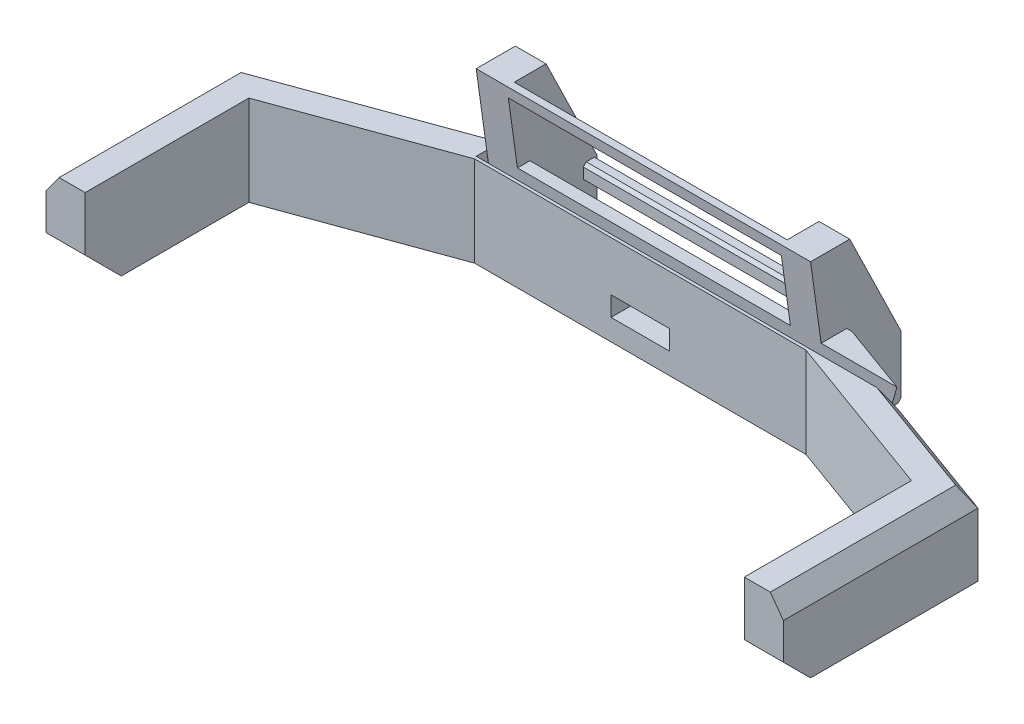
SolidWorks part; units mm, degrees
ref_plane "Front Plane" through (0, 0, 0) normal (0, 0, 1) x (1, 0, 0)
ref_plane "Top Plane" through (0, 0, 0) normal (0, 1, 0) x (1, 0, 0)
ref_plane "Right Plane" through (0, 0, 0) normal (1, 0, 0) x (0, 0, -1)
sketch "Sketch2" plane through (0, 0, 0) normal (0, 1, 0) x (1, 0, 0)
  line L0 (-1100, -366.1545) -> (-1100, 177.4707)
  line L1 (-1100, 177.4707) -> (-550, 377.4707)
  line L2 (-550, 377.4707) -> (550, 377.4707)
  line L3 (550, 377.4707) -> (1100, 177.4707)
  line L4 (1100, 177.4707) -> (1100, -377.4707)
  line L5 (0, -626.2815) -> (0, 867.8221) construction
  line L6 (-1230, -366.1545) -> (-1230, 268.5262)
  line L7 (-1230, 268.5262) -> (-572.9027, 507.4707)
  line L8 (-572.9027, 507.4707) -> (572.9027, 507.4707)
  line L9 (572.9027, 507.4707) -> (1230, 268.5262)
  line L10 (1230, 268.5262) -> (1230, -377.4707)
  line L11 (-1230, -366.1545) -> (-1100, -366.1545)
  line L12 (1100, -377.4707) -> (1230, -377.4707)
  point P9 (0, 377.4707)
  dimension "D1" = 130
extrude "Boss-Extrude1" add sketch "Sketch2" along normal blind 300
fillet "Chamfer1" radius 30 5 edges at (-901.4514, 0, -387.9984) (-1230, 0, 48.8141) (0, 0, -507.4707) (1230, 0, 54.4722) (901.4514, 0, -387.9984) profile chamfer
chamfer "Chamfer2" distance 120 angle 45 2 edges at (-1150, 0, 366.1545) (1150, 0, 377.4707)
sketch "Sketch3" plane through (0, 0, -507.4707) normal (0, 0, -1) x (-1, 0, 0)
  line L0 (567.6175, 0) -> (-567.6175, 0) construction
  line L1 (-555.1604, 551.8427) -> (-453.2203, 551.8427)
  line L2 (-555.1604, 551.8427) -> (-555.1604, 0)
  line L3 (-555.1604, 0) -> (-453.2203, 0)
  line L4 (-453.2203, 551.8427) -> (-453.2203, 0)
  line L5 (0, 857.663) -> (0, -558.4781) construction
  line L6 (555.1604, 551.8427) -> (453.2203, 551.8427)
  line L7 (555.1604, 551.8427) -> (555.1604, 0)
  line L8 (555.1604, 0) -> (453.2203, 0)
  line L9 (453.2203, 551.8427) -> (453.2203, 0)
  point P13 (-555.1604, 0)
extrude "Boss-Extrude2" add sketch "Sketch3" along normal blind 180 and the other way blind 120
sketch "Sketch5" plane through (-555.1604, 0, 0) normal (-1, 0, 0) x (0, 0, 1)
  line L0 (-387.4707, 551.8427) -> (-433.4972, 219.8641)
  line L1 (-433.4972, 219.8641) -> (-387.4707, 300)
  line L2 (-387.4707, 300) -> (-387.4707, 551.8427)
extrude "Cut-Extrude7" cut sketch "Sketch5" against normal through all
chamfer "Chamfer3" distance 170 angle 64 2 edges at (-504.1903, 551.8427, -687.4707) (504.1903, 551.8427, -687.4707)
sketch "Sketch6" plane through (-453.2203, 0, 0) normal (1, 0, 0) x (0, 0, -1)
  line L0 (387.4707, 551.8427) -> (393.758, 506.4936)
  line L1 (422.3869, 300) -> (387.4707, 551.8427) construction
  line L2 (393.758, 506.4936) -> (421.6998, 506.4936)
  line L3 (421.6998, 506.4936) -> (421.6998, 551.8427)
  line L4 (387.4707, 551.8427) -> (517.4707, 551.8427) construction
  line L5 (421.6998, 551.8427) -> (387.4707, 551.8427)
  line L6 (687.4707, 203.291) -> (641.0284, 203.291)
  line L7 (641.0284, 203.291) -> (641.0284, 148.3016)
  line L8 (641.0284, 148.3016) -> (687.4707, 148.3016)
  line L9 (687.4707, 203.291) -> (687.4707, 0) construction
  line L10 (687.4707, 148.3016) -> (687.4707, 203.291)
  line L11 (687.4707, 0) -> (641.0284, 0)
  line L12 (477.4707, 0) -> (687.4707, 0) construction
  line L13 (641.0284, 0) -> (641.0284, 57.6558)
  line L14 (641.0284, 57.6558) -> (687.4707, 57.6558)
  line L15 (687.4707, 57.6558) -> (687.4707, 0)
extrude "Boss-Extrude3" add sketch "Sketch6" along normal up to surface (906.4405 mm away) up to face at (453.2203, 242.1221, -524.3352)
chamfer "Chamfer5" distance 10 angle 45 11 edges at (0, 506.4936, -421.6998) (0, 506.4936, -393.758) (0, 551.8427, -421.6998) (0, 148.3016, -641.0284) (0, 148.3016, -687.4707) (0, 57.6558, -641.0284) (0, 0, -687.4707) (0, 0, -641.0284) (0, 57.6558, -687.4707) (0, 203.291, -641.0284) (0, 203.291, -687.4707)
sketch "Sketch7" plane through (0, 0, -507.4707) normal (0, 0, -1) x (-1, 0, 0)
  line L0 (453.2203, 148.3016) -> (-453.2203, 148.3016) construction
  line L1 (-179.9048, 148.3016) -> (179.9048, 148.3016)
  line L2 (-179.9048, 148.3016) -> (-179.9048, 57.6558)
  line L3 (-179.9048, 57.6558) -> (179.9048, 57.6558)
  line L4 (179.9048, 148.3016) -> (179.9048, 57.6558)
  line L5 (-453.2203, 57.6558) -> (453.2203, 57.6558) construction
  line L6 (-453.2203, 229.9647) -> (-453.2203, -108.7143) construction
  line L7 (-453.2203, 551.8427) -> (-453.2203, 203.291) construction
  line L8 (453.2203, 271.8323) -> (453.2203, -96.7521) construction
  line L9 (453.2203, 203.291) -> (453.2203, 551.8427) construction
  line L10 (0, -117.6859) -> (0, 348.0911) construction
extrude "Boss-Extrude4" add sketch "Sketch7" along normal blind 20
sketch "Sketch8" plane through (0, 0, -527.4707) normal (0, 0, -1) x (-1, 0, 0)
  line L0 (0, 287.0499) -> (0, -219.5145) construction
  line L1 (-97.5, 135.4787) -> (97.5, 135.4787)
  line L2 (-97.5, 135.4787) -> (-97.5, 70.4787)
  line L3 (-97.5, 70.4787) -> (97.5, 70.4787)
  line L4 (97.5, 135.4787) -> (97.5, 70.4787)
  line L5 (-179.9048, 102.9787) -> (179.9048, 102.9787) construction
  line L6 (-179.9048, 148.3016) -> (-179.9048, 57.6558) construction
  line L7 (179.9048, 57.6558) -> (179.9048, 148.3016) construction
  dimension "D1" = 65
  dimension "D2" = 195
extrude "Cut-Extrude8" cut sketch "Sketch8" against normal blind 392
sketch "Sketch9" plane through (0, 0, -421.6998) normal (0, 0, -1) x (-1, 0, 0)
  line L1 (-420.801, 536.7594) -> (-296.46, 536.7594)
  line L2 (-420.801, 536.7594) -> (-420.801, 520.5222)
  line L3 (-420.801, 520.5222) -> (-296.46, 520.5222)
  line L4 (-296.46, 536.7594) -> (-296.46, 520.5222)
  line L6 (-180.801, 520.5222) -> (-56.46, 520.5222)
  line L11 (-180.801, 536.7594) -> (-56.46, 536.7594)
  line L12 (-56.46, 536.7594) -> (-56.46, 520.5222)
  line L13 (-180.801, 536.7594) -> (-180.801, 520.5222)
  line L14 (59.199, 520.5222) -> (183.54, 520.5222)
  line L15 (59.199, 536.7594) -> (183.54, 536.7594)
  line L16 (183.54, 536.7594) -> (183.54, 520.5222)
  line L17 (59.199, 536.7594) -> (59.199, 520.5222)
  line L18 (299.199, 520.5222) -> (423.54, 520.5222)
  line L19 (299.199, 536.7594) -> (423.54, 536.7594)
  line L20 (423.54, 536.7594) -> (423.54, 520.5222)
  line L21 (299.199, 536.7594) -> (299.199, 520.5222)
  dimension "D1" = 4
extrude "Boss-Extrude5" add sketch "Sketch9" along normal blind 5
chamfer "Chamfer6" distance 60 angle 36 5 edges at (-1230, 300, 48.8141) (-901.4514, 300, -387.9984) (0, 300, -507.4707) (1066.4514, 300, -327.9984) (1230, 300, 54.4722)
